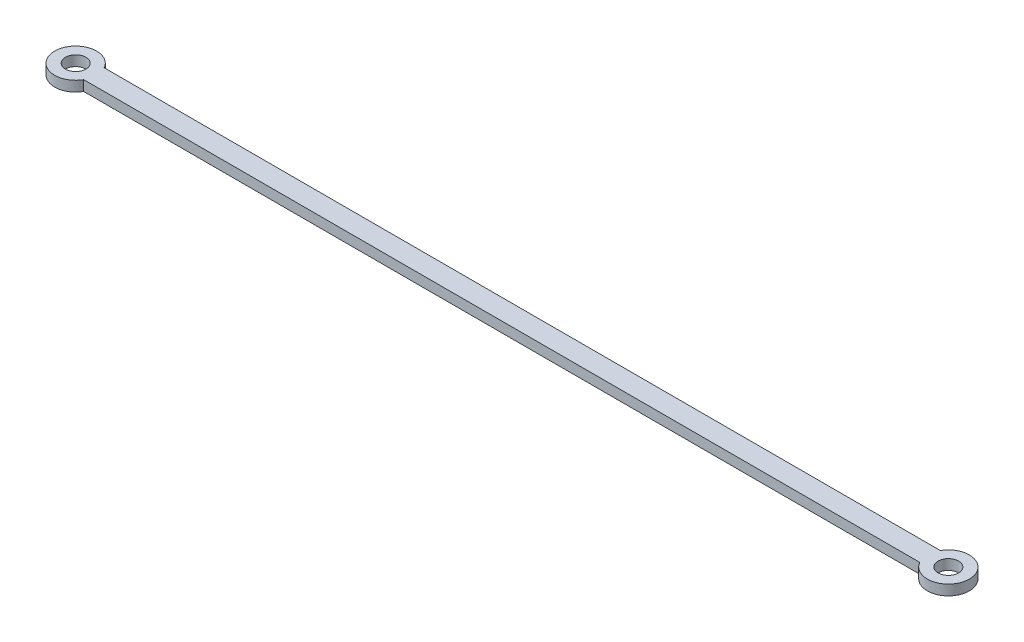
SolidWorks part; units mm, degrees
ref_plane "Front Plane" through (0, 0, 0) normal (0, 0, 1) x (1, 0, 0)
ref_plane "Top Plane" through (0, 0, 0) normal (0, 1, 0) x (1, 0, 0)
ref_plane "Right Plane" through (0, 0, 0) normal (1, 0, 0) x (0, 0, -1)
sketch "Sketch4" plane through (0, 0, 0) normal (0, 1, 0) x (1, 0, 0)
  line L0 (0, 0) -> (0, -116.8928) construction
  line L1 (-814.5, 20) -> (814.5, 20)
  line L2 (-814.5, 20) -> (-814.5, -20)
  line L3 (-814.5, -20) -> (814.5, -20)
  line L4 (814.5, 20) -> (814.5, -20)
  line L5 (-814.5, 20) -> (814.5, -20) construction
  line L6 (-814.5, -20) -> (814.5, 20) construction
  circle A1 centre (-850.1342, 0) radius 40.8631
  circle A2 centre (850.1342, 0) radius 40.8631
  point P0 (0, 0)
  dimension "D1" = 40
  dimension "D2" = 1629
extrude "Boss-Extrude1" add sketch "Sketch4" along normal blind 20 contours L3 A2 L1 A1 | A2 L4 | A2 L4
sketch "Sketch6" plane through (0, 0, 0) normal (0, -1, 0) x (1, 0, 0)
  circle A0 centre (-850.1342, 0) radius 20
  circle A1 centre (850.1342, 0) radius 20
  dimension "D1" = 40
extrude "Cut-Extrude1" cut sketch "Sketch6" against normal up to next contours A1 | A0
